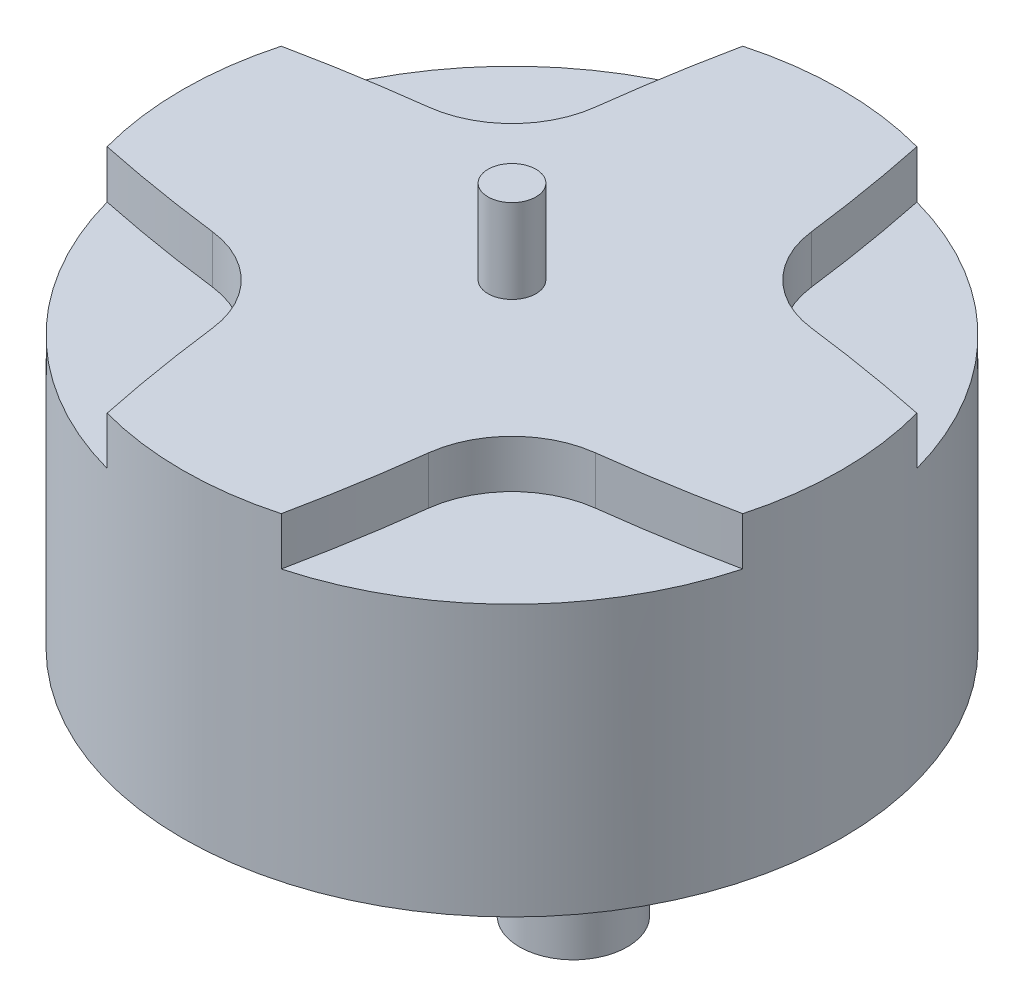
SolidWorks part; units mm, degrees
ref_plane "前视基准面" through (0, 0, 0) normal (0, 0, 1) x (1, 0, 0)
ref_plane "上视基准面" through (0, 0, 0) normal (0, 1, 0) x (1, 0, 0)
ref_plane "右视基准面" through (0, 0, 0) normal (1, 0, 0) x (0, 0, -1)
sketch "草图1" plane through (0, 0, 0) normal (0, 1, 0) x (1, 0, 0)
  line L0 (0, 7) -> (-6.0622, -3.5) construction
  line L7 (-6.0622, -3.5) -> (6.0622, -3.5) construction
  line L8 (6.0622, -3.5) -> (0, 7) construction
  line L9 (-1.9486, 5.875) -> (-6.0622, -1.25)
  line L10 (-4.1136, -4.625) -> (4.1136, -4.625)
  line L11 (6.0622, -1.25) -> (1.9486, 5.875)
  line L12 (-6.0622, -1.25) -> (-8.0107, -4.625) construction
  line L13 (0, 9.25) -> (-8.0107, -4.625) construction
  line L14 (-8.0107, -4.625) -> (-4.1136, -4.625) construction
  line L15 (-8.0107, -4.625) -> (8.0107, -4.625) construction
  line L16 (4.1136, -4.625) -> (8.0107, -4.625) construction
  line L17 (8.0107, -4.625) -> (6.0622, -1.25) construction
  line L18 (8.0107, -4.625) -> (0, 9.25) construction
  line L19 (0, 9.25) -> (-1.9486, 5.875) construction
  line L20 (1.9486, 5.875) -> (0, 9.25) construction
  arc A0 (1.9486, 5.875) -> (-1.9486, 5.875) centre (0, 7) ccw
  arc A1 (4.1136, -4.625) -> (6.0622, -1.25) centre (6.0622, -3.5) ccw
  arc A2 (-6.0622, -1.25) -> (-4.1136, -4.625) centre (-6.0622, -3.5) ccw
  arc A3 (-1.9486, 5.875) -> (-1.125, 5.0514) centre (0, 7) ccw construction
  arc A4 (-1.125, 5.0514) -> (1.125, 5.0514) centre (0, 7) ccw construction
  arc A5 (4.9372, -1.5514) -> (3.8122, -3.5) centre (6.0622, -3.5) ccw construction
  arc A6 (-3.8122, -3.5) -> (-4.9372, -1.5514) centre (-6.0622, -3.5) ccw construction
  arc A7 (-4.9372, -1.5514) -> (-6.0622, -1.25) centre (-6.0622, -3.5) ccw construction
  arc A8 (-4.1136, -4.625) -> (-3.8122, -3.5) centre (-6.0622, -3.5) ccw construction
  arc A9 (3.8122, -3.5) -> (4.1136, -4.625) centre (6.0622, -3.5) ccw construction
  arc A10 (6.0622, -1.25) -> (4.9372, -1.5514) centre (6.0622, -3.5) ccw construction
  arc A11 (1.125, 5.0514) -> (1.9486, 5.875) centre (0, 7) ccw construction
  circle A12 centre (0, 7) radius 1.25
  circle A13 centre (-6.0622, -3.5) radius 1.25
  circle A14 centre (6.0622, -3.5) radius 1.25
  dimension "D3" = 4.5
  dimension "D4" = 2.5
  dimension "D1" = 7
  dimension "D2" = 7
extrude "凸台-拉伸1" add sketch "草图1" along normal blind 2.5
fillet "圆角1" radius 2 6 edges at (1.9486, 1.25, -5.875) (6.0622, 1.25, 1.25) (4.1136, 1.25, 4.625) (-4.1136, 1.25, 4.625) (-6.0622, 1.25, 1.25) (-1.9486, 1.25, -5.875)
sketch "草图2" plane through (0, 2.5, 0) normal (0, 1, 0) x (1, 0, 0)
  circle A0 centre (0, 0) radius 4.625
extrude "凸台-拉伸2" add sketch "草图2" along normal blind 13.7
sketch "草图3" plane through (0, 16.2, 0) normal (0, 1, 0) x (1, 0, 0)
  circle A0 centre (0, 0) radius 1
  dimension "D1" = 2
extrude "凸台-拉伸3" add sketch "草图3" along normal blind 5.5
sketch "草图4" plane through (0, 16.2, 0) normal (0, 1, 0) x (1, 0, 0)
  arc A0 (-3.6328, -13.2614) -> (3.6328, -13.2614) centre (0, 0) ccw
  arc A1 (-13.2614, 3.6328) -> (-4.821, 4.821) centre (0, -60) cw
  arc A2 (-3.6328, 13.2614) -> (-4.821, 4.821) centre (60, 0) ccw
  arc A3 (-13.2614, -3.6328) -> (-4.821, -4.821) centre (0, 60) ccw
  arc A4 (3.6328, 13.2614) -> (4.821, 4.821) centre (-60, 0) cw
  circle A5 centre (0, 0) radius 1 construction
  arc A6 (-13.2614, -3.6328) -> (-3.6328, -13.2614) centre (0, 0) ccw construction
  arc A7 (-3.6328, 13.2614) -> (-13.2614, 3.6328) centre (0, 0) ccw construction
  arc A8 (-13.2614, 3.6328) -> (-13.2614, -3.6328) centre (0, 0) ccw
  arc A9 (13.2614, 3.6328) -> (3.6328, 13.2614) centre (0, 0) ccw construction
  arc A10 (3.6328, 13.2614) -> (-3.6328, 13.2614) centre (0, 0) ccw
  arc A11 (3.6328, -13.2614) -> (13.2614, -3.6328) centre (0, 0) ccw construction
  arc A12 (13.2614, -3.6328) -> (13.2614, 3.6328) centre (0, 0) ccw
  arc A13 (-4.821, -4.821) -> (4.821, -4.821) centre (0, 60) ccw construction
  arc A14 (4.821, -4.821) -> (13.2614, -3.6328) centre (0, 60) ccw
  arc A15 (4.821, 4.821) -> (4.821, -4.821) centre (-60, 0) cw construction
  arc A16 (4.821, -4.821) -> (3.6328, -13.2614) centre (-60, 0) cw
  arc A17 (-4.821, 4.821) -> (4.821, 4.821) centre (0, -60) cw construction
  arc A18 (4.821, 4.821) -> (13.2614, 3.6328) centre (0, -60) cw
  arc A19 (-4.821, 4.821) -> (-4.821, -4.821) centre (60, 0) ccw construction
  arc A20 (-4.821, -4.821) -> (-3.6328, -13.2614) centre (60, 0) ccw
  point P17 (-49.9837, 1.2762)
  point P18 (0, 0)
  point P19 (0, 0)
  point P20 (0, 0)
  dimension "D1" = 27.5
  dimension "D6" = 65
  dimension "D7" = 65
  dimension "D8" = 65
  dimension "D9" = 65
  dimension "D2" = 60
  dimension "D3" = 60
  dimension "D4" = 60
  dimension "D5" = 60
extrude "凸台-拉伸4" add sketch "草图4" along normal blind 2
sketch "草图5" plane through (0, 16.2, 0) normal (0, -1, 0) x (1, 0, 0)
  circle A0 centre (0, 0) radius 13.75
extrude "凸台-拉伸5" add sketch "草图5" along normal blind 11.3
fillet "圆角2" radius 4 4 edges at (4.821, 17.2, -4.821) (4.821, 17.2, 4.821) (-4.821, 17.2, 4.821) (-4.821, 17.2, -4.821)
